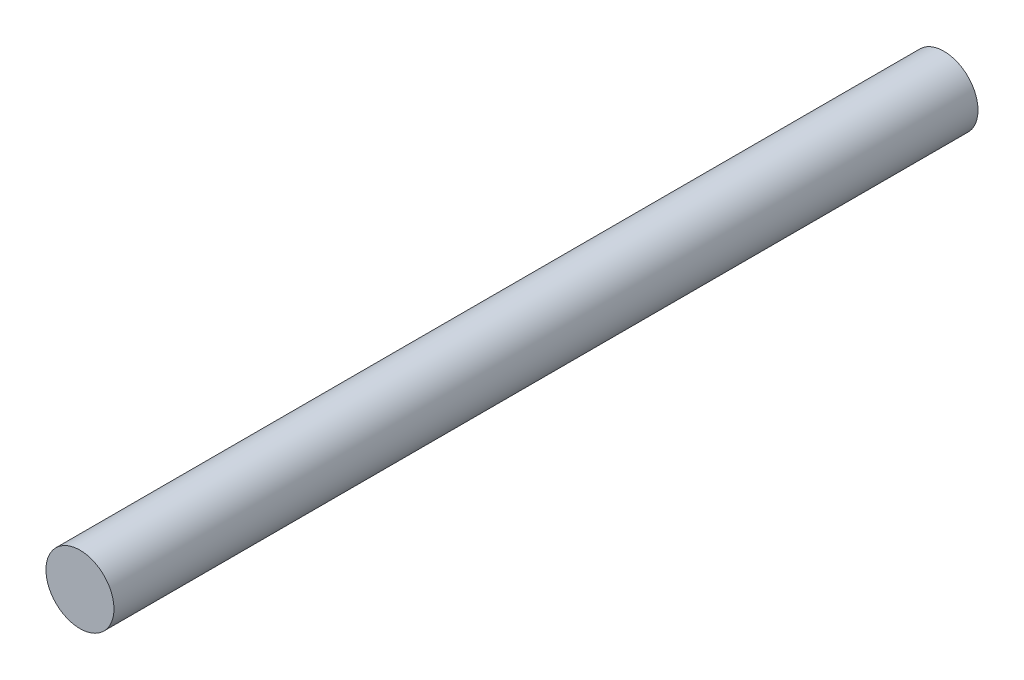
SolidWorks part; units mm, degrees
material "AISI 1020"
ref_plane "Front Plane" through (0, 0, 0) normal (0, 0, 1) x (1, 0, 0)
ref_plane "Top Plane" through (0, 0, 0) normal (0, 1, 0) x (1, 0, 0)
ref_plane "Right Plane" through (0, 0, 0) normal (1, 0, 0) x (0, 0, -1)
sketch "Sketch2" plane through (0, 0, 0) normal (0, 0, 1) x (1, 0, 0)
  circle A0 centre (0, 0) radius 4.5
ref_plane "Plane1" through (0, 0, 25.4) normal (0, 0, 1) x (1, 0, 0)
sketch "Sketch3" plane through (0, 0, 25.4) normal (0, 0, 1) x (1, 0, 0)
  line L0 (-3.9226, 2.2053) -> (3.9226, 2.2053)
  circle A0 centre (0, 0) radius 4.5
ref_plane "Plane2" through (0, 0, 88.9) normal (0, 0, 1) x (1, 0, 0)
sketch "Sketch4" plane through (0, 0, 88.9) normal (0, 0, 1) x (1, 0, 0)
  circle A0 centre (0, 0) radius 4.5
extrude "Boss-Extrude4" add sketch "Sketch4" against normal blind 114.3 contours A0
